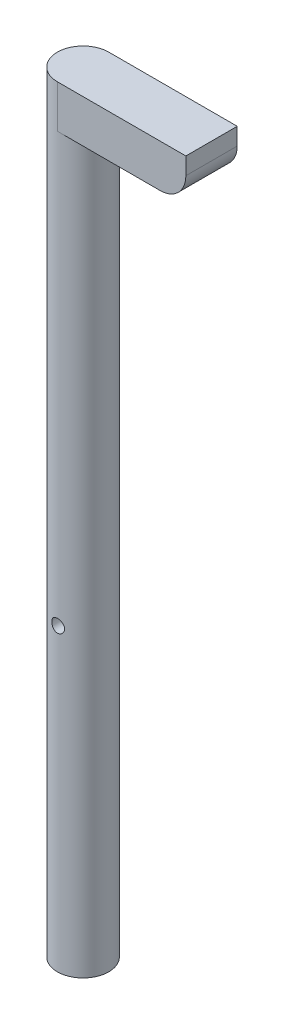
SolidWorks part; units mm, degrees
ref_plane "Front Plane" through (0, 0, 0) normal (0, 0, 1) x (1, 0, 0)
ref_plane "Top Plane" through (0, 0, 0) normal (0, 1, 0) x (1, 0, 0)
ref_plane "Right Plane" through (0, 0, 0) normal (1, 0, 0) x (0, 0, -1)
sketch "Sketch1" plane through (0, 0, 0) normal (0, 1, 0) x (1, 0, 0)
  circle A0 centre (0, 0) radius 3
  dimension "D1" = 6
extrude "Boss-Extrude1" add sketch "Sketch1" against normal blind 90
sketch "Sketch2" plane through (0, 0, 0) normal (0, 1, 0) x (1, 0, 0)
  line L0 (0, 0) -> (19.1175, 0) construction
  line L1 (0, 0) -> (0, 3)
  line L2 (15, 3) -> (0, 3)
  line L3 (15, 3) -> (15, -3)
  line L4 (15, -3) -> (0, -3)
  line L5 (0, -3) -> (0, 0)
  circle A0 centre (0, 0) radius 3 construction
  dimension "D1" = 6
  dimension "D2" = 15
extrude "Boss-Extrude2" add sketch "Sketch2" against normal blind 5
fillet "Fillet2" radius 3 1 edges at (15, -5, 0)
sketch "Sketch5" plane through (0, 0, 3) normal (0, 0, 1) x (1, 0, 0)
  line L0 (0, 0) -> (0, -93.3902) construction
  line L1 (0, -5) -> (12, -5) construction
  circle A0 centre (0, -55) radius 0.75
  dimension "D1" = 1.5
  dimension "D2" = 50
extrude "Cut-Extrude2" cut sketch "Sketch5" against normal through all
